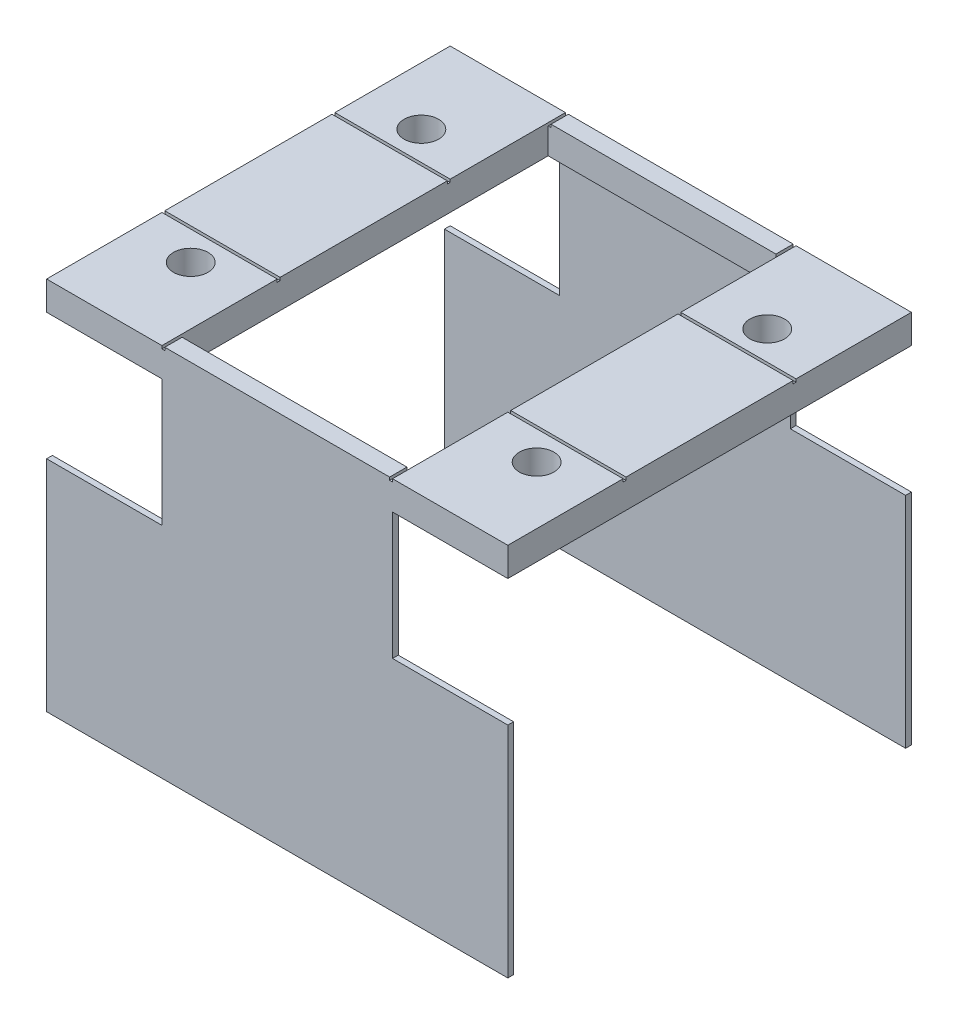
SolidWorks part; units mm, degrees
ref_plane "前视基准面" through (0, 0, 0) normal (0, 0, 1) x (1, 0, 0)
ref_plane "上视基准面" through (0, 0, 0) normal (0, 1, 0) x (1, 0, 0)
ref_plane "右视基准面" through (0, 0, 0) normal (1, 0, 0) x (0, 0, -1)
other "Configuration Table"
sketch "草图1" plane through (0, 0, 0) normal (0, 1, 0) x (1, 0, 0)
  line L0 (-30, 19.7785) -> (-30, -49980.2215) construction
  line L1 (-40, 35) -> (40, 35)
  line L2 (-40, 35) -> (-40, -35)
  line L3 (-40, -35) -> (40, -35)
  line L4 (40, 35) -> (40, -35)
  line L5 (-40, 35) -> (40, -35) construction
  line L6 (-40, -35) -> (40, 35) construction
  line L7 (30, 11.0728) -> (30, -49988.9272) construction
  line L8 (30.6083, 20) -> (-49969.3917, 20) construction
  line L9 (-6.3319, -20) -> (49993.6681, -20) construction
  line L10 (-20, 8.6738) -> (-20, -49991.3262) construction
  line L11 (-5.1939, 32) -> (49994.8061, 32) construction
  line L12 (20, 4.1032) -> (20, -49995.8968) construction
  line L13 (-0.5194, -32) -> (-50000.5194, -32) construction
  line L14 (-20, 32) -> (-20, -32)
  line L15 (-20, -32) -> (20, -32)
  line L16 (20, -32) -> (20, 32)
  line L17 (20, 32) -> (-20, 32)
  circle A0 centre (-30, 20) radius 3
  circle A1 centre (-30, -20) radius 3
  circle A2 centre (30, -20) radius 3
  circle A3 centre (30, 20) radius 3
  point P0 (0, 0)
  dimension "D7" = 6
  dimension "D8" = 6
  dimension "D9" = 6
  dimension "D10" = 6
  dimension "D1" = 80
  dimension "D2" = 70
  dimension "D3" = 10
  dimension "D4" = 10
  dimension "D5" = 15
  dimension "D6" = 15
  dimension "D11" = 20
  dimension "D12" = 20
  dimension "D13" = 3
  dimension "D14" = 3
extrude "凸台-拉伸1" add sketch "草图1" along normal blind 5
sketch "草图2" plane through (0, 0, 0) normal (0, -1, 0) x (1, 0, 0)
  line L0 (-40, -35) -> (-40, 35) construction
  line L1 (40, 35) -> (40, -35) construction
  line L2 (-40, 35) -> (40, 35) construction
  line L3 (-40, 35) -> (40, 35)
  line L4 (-40, 35) -> (-40, 34)
  line L5 (-40, 34) -> (40, 34)
  line L6 (40, 35) -> (40, 34)
  line L7 (40, -35) -> (-40, -35) construction
  line L8 (-40, -35) -> (40, -35)
  line L9 (-40, -35) -> (-40, -34)
  line L10 (-40, -34) -> (40, -34)
  line L11 (40, -35) -> (40, -34)
  point P0 (40, 34)
  dimension "D3" = 1
  dimension "D4" = 1
extrude "凸台-拉伸2" add sketch "草图2" along normal blind 60
sketch "草图3" plane through (0, 0, 35) normal (0, 0, 1) x (1, 0, 0)
  line L0 (-40, 0) -> (49960, 0) construction
  line L1 (40, 0) -> (20, 0)
  line L2 (40, 0) -> (40, -22)
  line L3 (40, -22) -> (20, -22)
  line L4 (20, 0) -> (20, -22)
  line L5 (-40, 0) -> (-20, 0)
  line L6 (-40, 0) -> (-40, -22)
  line L7 (-40, -22) -> (-20, -22)
  line L8 (-20, 0) -> (-20, -22)
  line L9 (20, -6.0374) -> (20, -50006.0374) construction
  line L10 (-20, -8.3433) -> (-20, -50008.3433) construction
  line L11 (-40, 5) -> (-40, -60) construction
  line L12 (40, 5) -> (40, -60) construction
  dimension "D1" = 20
  dimension "D2" = 20
  dimension "D3" = 22
  dimension "D4" = 22
extrude "切除-拉伸1" cut sketch "草图3" against normal through all
sketch "草图5" plane through (0, 5, 0) normal (0, 1, 0) x (1, 0, 0)
  line L0 (40, 35) -> (-40, 35) construction
  line L1 (-19.5, 35) -> (-20, 35)
  line L2 (-19.5, 35) -> (-19.5, -35)
  line L3 (-19.5, -35) -> (-20, -35)
  line L4 (-20, 35) -> (-20, -35)
  line L5 (-40, -35) -> (40, -35) construction
  line L6 (20, 35) -> (19.5, 35)
  line L7 (20, 35) -> (20, -35)
  line L8 (20, -35) -> (19.5, -35)
  line L9 (19.5, 35) -> (19.5, -35)
  dimension "D1" = 0.5
  dimension "D2" = 0.5
extrude "切除-拉伸2" cut sketch "草图5" against normal blind 0.5
sketch "草图6" plane through (0, 5, 0) normal (0, 1, 0) x (1, 0, 0)
  line L0 (-40, 35) -> (-40, -35) construction
  line L1 (-40, -15) -> (40, -15)
  line L2 (-40, -15) -> (-40, -14.5)
  line L3 (-40, -14.5) -> (40, -14.5)
  line L4 (40, -15) -> (40, -14.5)
  line L5 (40, -35) -> (40, 35) construction
  line L6 (-40, -35) -> (-20, -35) construction
  line L7 (40, 15) -> (-40, 15)
  line L8 (40, 15) -> (40, 14.5)
  line L9 (40, 14.5) -> (-40, 14.5)
  line L10 (-40, 15) -> (-40, 14.5)
  line L11 (-20, 35) -> (-40, 35) construction
  dimension "D1" = 0.5
  dimension "D2" = 0.5
  dimension "D3" = 20
  dimension "D4" = 20
extrude "切除-拉伸3" cut sketch "草图6" against normal blind 0.5
